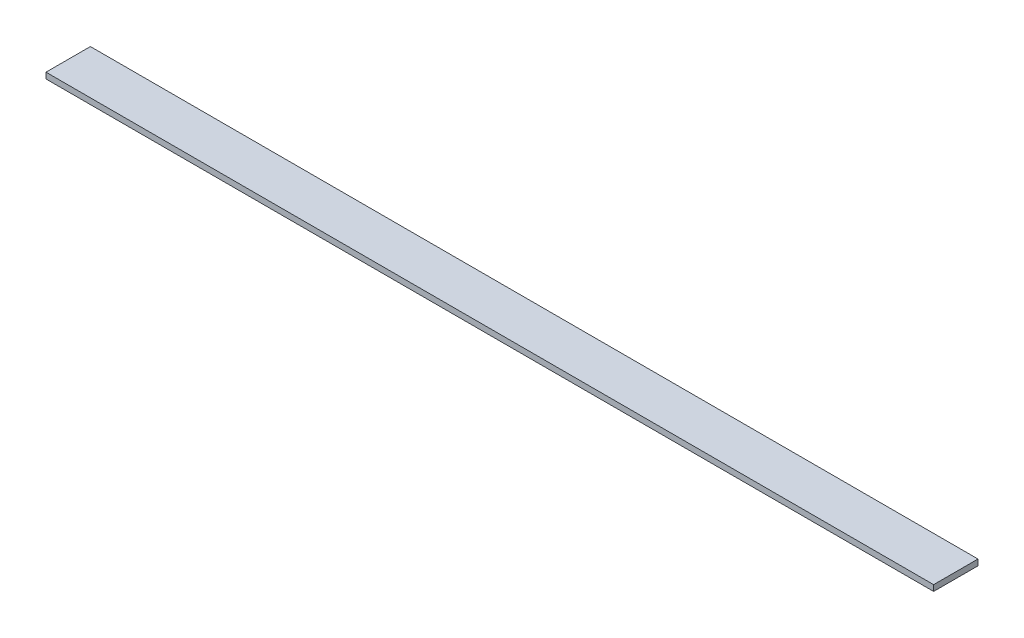
SolidWorks part; units mm, degrees
ref_plane "Front Plane" through (0, 0, 0) normal (0, 0, 1) x (1, 0, 0)
ref_plane "Top Plane" through (0, 0, 0) normal (0, 1, 0) x (1, 0, 0)
ref_plane "Right Plane" through (0, 0, 0) normal (1, 0, 0) x (0, 0, -1)
sketch "Sketch1" plane through (0, 0, 0) normal (1, 0, 0) x (0, 0, -1)
  line L1 (-7.5, 1) -> (7.5, 1)
  line L2 (-7.5, 1) -> (-7.5, -1)
  line L3 (-7.5, -1) -> (7.5, -1)
  line L4 (7.5, 1) -> (7.5, -1)
  line L5 (-7.5, 1) -> (7.5, -1) construction
  line L6 (-7.5, -1) -> (7.5, 1) construction
  point P0 (0, 0)
  dimension "D1" = 15
  dimension "D2" = 2
extrude "Boss-Extrude1" add sketch "Sketch1" along normal blind 300
